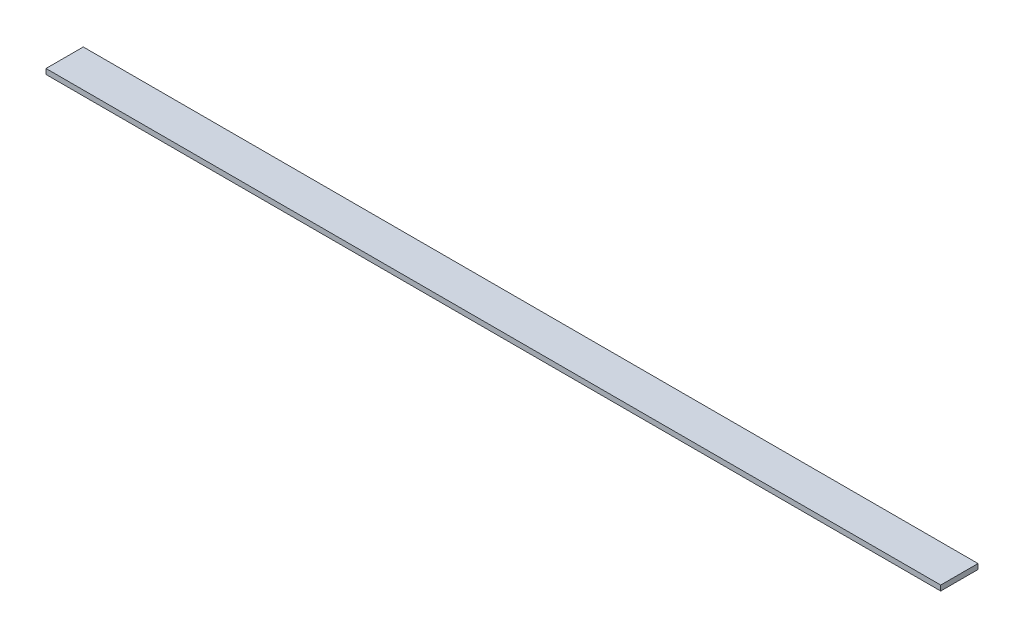
SolidWorks part; units mm, degrees
ref_plane "Front Plane" through (0, 0, 0) normal (0, 0, 1) x (1, 0, 0)
ref_plane "Top Plane" through (0, 0, 0) normal (0, 1, 0) x (1, 0, 0)
ref_plane "Right Plane" through (0, 0, 0) normal (1, 0, 0) x (0, 0, -1)
sketch "Sketch1" plane through (0, 0, 0) normal (0, 1, 0) x (1, 0, 0)
  line L1 (-60, -2.5) -> (60, -2.5)
  line L2 (-60, -2.5) -> (-60, 2.5)
  line L3 (-60, 2.5) -> (60, 2.5)
  line L4 (60, -2.5) -> (60, 2.5)
  line L5 (-60, -2.5) -> (60, 2.5) construction
  line L6 (-60, 2.5) -> (60, -2.5) construction
  point P0 (0, 0)
  dimension "D1" = 5
  dimension "D2" = 120
extrude "Boss-Extrude1" add sketch "Sketch1" along normal blind 0.7
